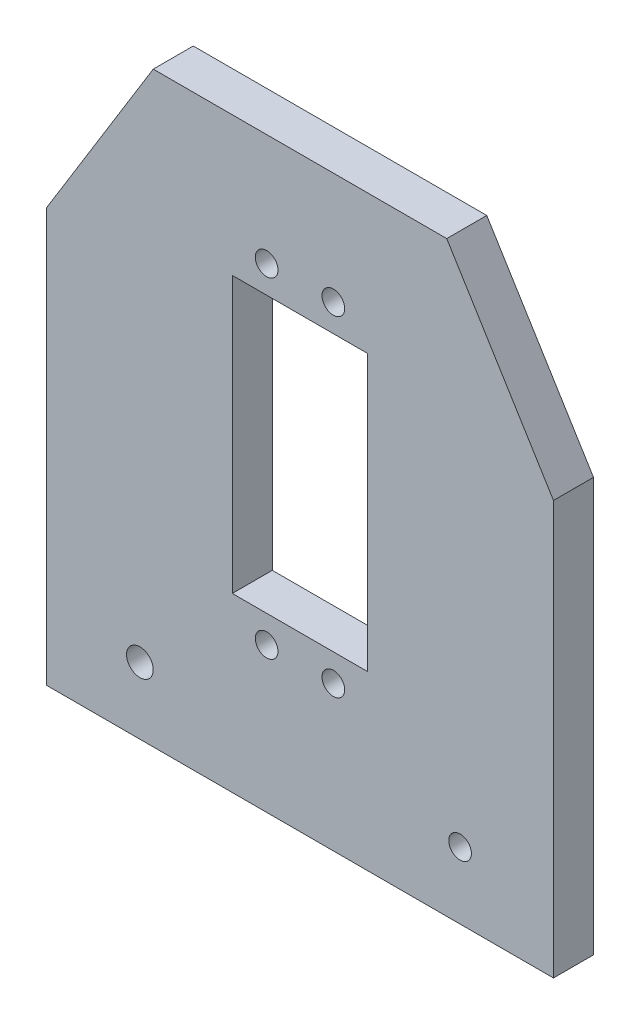
SolidWorks part; units mm, degrees
ref_plane "Спереди" through (0, 0, 0) normal (0, 0, 1) x (1, 0, 0)
ref_plane "Сверху" through (0, 0, 0) normal (0, 1, 0) x (1, 0, 0)
ref_plane "Справа" through (0, 0, 0) normal (1, 0, 0) x (0, 0, -1)
other "Configuration Table"
sketch "Эскиз1" plane through (0, 0, 0) normal (0, 0, 1) x (1, 0, 0)
  line L0 (-38, 0) -> (38, 0)
  line L1 (38, 0) -> (38, 62)
  line L2 (38, 62) -> (22, 88)
  line L3 (22, 88) -> (-22, 88)
  line L4 (-22, 88) -> (-38, 62)
  line L5 (-38, 62) -> (-38, 0)
  line L7 (-10.15, 25.85) -> (10.15, 25.85)
  line L8 (-10.15, 25.85) -> (-10.15, 67.15)
  line L9 (-10.15, 67.15) -> (10.15, 67.15)
  line L10 (10.15, 25.85) -> (10.15, 67.15)
  circle A0 centre (-5, 21.75) radius 1.7
  circle A1 centre (-5, 71.25) radius 1.7
  circle A2 centre (5, 21.75) radius 1.7
  circle A3 centre (5, 71.25) radius 1.7
  circle A4 centre (-24, 10) radius 2
  circle A5 centre (24, 10) radius 1.7
extrude "07_Tilt_drive_cheek" add sketch "Эскиз1" along normal blind 6
